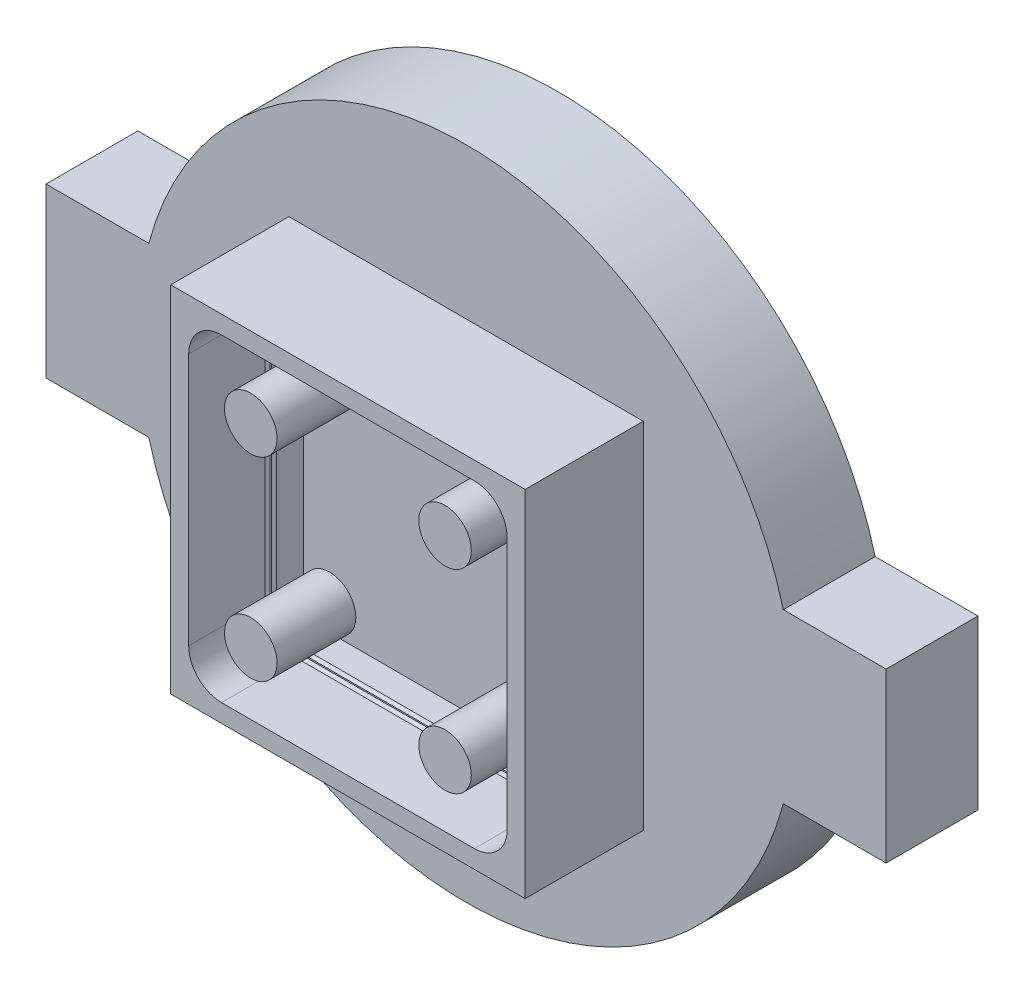
SolidWorks part; units mm, degrees
material "PLA"
ref_plane "Front Plane" through (0, 0, 0) normal (0, 0, 1) x (1, 0, 0)
ref_plane "Top Plane" through (0, 0, 0) normal (0, 1, 0) x (1, 0, 0)
ref_plane "Right Plane" through (0, 0, 0) normal (1, 0, 0) x (0, 0, -1)
sketch "Sketch1" plane through (0, 0, 0) normal (0, 0, 1) x (1, 0, 0)
  line L0 (-9.9216, -1.25) -> (-14.0216, -1.25) construction
  line L1 (14.0216, -1.25) -> (9.9216, -1.25) construction
  line L2 (14.0216, 1.25) -> (14.0216, -1.25) construction
  line L3 (-14.0216, -1.25) -> (-14.0216, 1.25) construction
  line L4 (-14.0216, 1.25) -> (-9.9216, 1.25) construction
  line L5 (9.9216, 1.25) -> (14.0216, 1.25) construction
  line L6 (-9.9216, -1.25) -> (-14.0216, -1.25)
  line L7 (14.0216, -1.25) -> (9.9216, -1.25)
  line L8 (14.0216, 1.25) -> (14.0216, -1.25)
  line L9 (-14.0216, -1.25) -> (-14.0216, 1.25)
  line L10 (-14.0216, 1.25) -> (-9.9216, 1.25)
  line L11 (9.9216, 1.25) -> (14.0216, 1.25)
  arc A0 (-9.9216, -1.25) -> (9.9216, -1.25) centre (0, 0) ccw construction
  arc A1 (9.9216, 1.25) -> (-9.9216, 1.25) centre (0, 0) ccw construction
  arc A2 (-9.9216, -1.25) -> (9.9216, -1.25) centre (0, 0) ccw
  arc A3 (9.9216, 1.25) -> (-9.9216, 1.25) centre (0, 0) ccw
  circle A4 centre (0, 0) radius 17.5
  dimension "D1" = 35
extrude "Boss-Extrude1" add sketch "Sketch1" along normal blind 3 contours A4
sketch "Sketch2" plane through (0, 0, 3) normal (0, 0, 1) x (1, 0, 0)
  circle A0 centre (0, 0) radius 17.5
extrude "Boss-Extrude2" add sketch "Sketch2" along normal blind 0.5
sketch "Sketch3" plane through (0, 0, 3.5) normal (0, 0, 1) x (1, 0, 0)
  line L1 (4.7, 4.7) -> (-4.7, 4.7)
  line L2 (4.7, 4.7) -> (4.7, -4.7)
  line L3 (4.7, -4.7) -> (-4.7, -4.7)
  line L4 (-4.7, 4.7) -> (-4.7, -4.7)
  line L5 (4.7, 4.7) -> (-4.7, -4.7) construction
  line L6 (4.7, -4.7) -> (-4.7, 4.7) construction
  line L7 (5.815, -5.815) -> (-5.815, -5.815)
  line L8 (5.815, -5.815) -> (5.815, 5.815)
  line L9 (5.815, 5.815) -> (-5.815, 5.815)
  line L10 (-5.815, -5.815) -> (-5.815, 5.815)
  line L11 (5.815, -5.815) -> (-5.815, 5.815) construction
  line L12 (5.815, 5.815) -> (-5.815, -5.815) construction
  line L13 (-6.75, -6.75) -> (6.75, -6.75)
  line L14 (-6.75, -6.75) -> (-6.75, 6.75)
  line L15 (-6.75, 6.75) -> (6.75, 6.75)
  line L16 (6.75, -6.75) -> (6.75, 6.75)
  line L17 (-6.75, -6.75) -> (6.75, 6.75) construction
  line L18 (-6.75, 6.75) -> (6.75, -6.75) construction
  circle A1 centre (0, 0) radius 17.5
  circle A2 centre (0, 0) radius 17.5 construction
  dimension "D2" = 9.4
  dimension "D3" = 11.63
  dimension "D4" = 13.5
  dimension "D1" = 0
extrude "Boss-Extrude3" add sketch "Sketch3" along normal blind 1.5 contours L1 L4 L3 L2 | L13 L16 L15 L14 L7 L10 L9 L8
fillet "Fillet1" radius 1 8 edges at (-5.815, -5.815, 4.25) (5.815, 5.815, 4.25) (-5.815, 5.815, 4.25) (4.7, -4.7, 4.25) (5.815, -5.815, 4.25) (-4.7, -4.7, 4.25) (-4.7, 4.7, 4.25) (4.7, 4.7, 4.25)
sketch "Sketch4" plane through (0, 0, 0) normal (0, 0, -1) x (-1, 0, 0)
  line L0 (0, -3.2) -> (0, -13.6813) construction
  line L1 (0, 0) -> (-15.8073, 0) construction
  line L2 (-16, 3.2) -> (-16, -3.2)
  line L3 (16, 3.2) -> (12.0835, 3.2)
  line L4 (16, 3.2) -> (16, -3.2)
  line L5 (16, -3.2) -> (12.0835, -3.2)
  line L7 (-12.0835, -3.2) -> (-16, -3.2)
  line L8 (-12.0835, 3.2) -> (-16, 3.2)
  arc A0 (12.0835, -3.2) -> (-12.0835, -3.2) centre (0, 0) cw
  arc A1 (12.0835, 3.2) -> (-12.0835, 3.2) centre (0, 0) ccw
  circle A2 centre (0, 0) radius 17.5
  circle A3 centre (0, 0) radius 17.5 construction
  dimension "D3" = 12.5
  dimension "D1" = 6.4
  dimension "D2" = 16
extrude "Cut-Extrude1" cut sketch "Sketch4" against normal blind 32.5
sketch "Sketch5" plane through (0, 0, 5) normal (0, 0, 1) x (1, 0, 0)
  circle A3 centre (0, 0) radius 3.94 construction
  circle A4 centre (-3.7, 3.7) radius 1
  circle A5 centre (3.7, 3.7) radius 1
  circle A6 centre (3.7, -3.7) radius 1
  circle A7 centre (-3.7, -3.7) radius 1
  arc A8 (-4.7, -3.7) -> (-3.7, -4.7) centre (-3.7, -3.7) ccw construction
  arc A9 (-3.7, 4.7) -> (-4.7, 3.7) centre (-3.7, 3.7) ccw construction
  dimension "D2" = 7.88
extrude "Boss-Extrude4" add sketch "Sketch5" along normal blind 3
sketch "Sketch6" plane through (0, 0, 8) normal (0, 0, 1) x (1, 0, 0)
  line L0 (0, 0) -> (0, -3.7) construction
  line L3 (0, 0) -> (3.3794, 0) construction
  line L14 (-6.065, 4.815) -> (-6.065, -4.815)
  line L15 (-4.815, -6.065) -> (4.815, -6.065)
  line L16 (6.065, -4.815) -> (6.065, 4.815)
  line L17 (4.815, 6.065) -> (-4.815, 6.065)
  line L18 (-6.065, 4.815) -> (-6.065, -4.815)
  line L19 (-4.815, -6.065) -> (4.815, -6.065)
  line L20 (6.065, -4.815) -> (6.065, 4.815)
  line L21 (4.815, 6.065) -> (-4.815, 6.065)
  line L38 (-6.75, -6.75) -> (6.75, -6.75)
  line L39 (6.75, -6.75) -> (6.75, 6.75)
  line L40 (6.75, 6.75) -> (-6.75, 6.75)
  line L41 (-6.75, 6.75) -> (-6.75, -6.75)
  line L46 (-6.75, -6.75) -> (6.75, -6.75)
  line L47 (6.75, -6.75) -> (6.75, 6.75)
  line L48 (6.75, 6.75) -> (-6.75, 6.75)
  line L49 (-6.75, 6.75) -> (-6.75, -6.75)
  arc A12 (-6.065, -4.815) -> (-4.815, -6.065) centre (-4.815, -4.815) ccw
  arc A13 (4.815, -6.065) -> (6.065, -4.815) centre (4.815, -4.815) ccw
  arc A14 (6.065, 4.815) -> (4.815, 6.065) centre (4.815, 4.815) ccw
  arc A15 (-4.815, 6.065) -> (-6.065, 4.815) centre (-4.815, 4.815) ccw
  arc A16 (-6.065, -4.815) -> (-4.815, -6.065) centre (-4.815, -4.815) ccw
  arc A17 (4.815, -6.065) -> (6.065, -4.815) centre (4.815, -4.815) ccw
  arc A18 (6.065, 4.815) -> (4.815, 6.065) centre (4.815, 4.815) ccw
  arc A19 (-4.815, 6.065) -> (-6.065, 4.815) centre (-4.815, 4.815) ccw
  dimension "D1" = 0.25
  dimension "D2" = 0
extrude "Boss-Extrude6" add sketch "Sketch6" against normal up to surface (3 mm away) up to face at (0, 0, 5)
chamfer "Chamfer1" distance 0.1 angle 45 16 edges at (-5.6989, 5.6989, 5) (0, 6.065, 5) (5.6989, 5.6989, 5) (6.065, 0, 5) (5.6989, -5.6989, 5) (0, -6.065, 5) (-5.6989, -5.6989, 5) (-6.065, 0, 5) (5.5221, 5.5221, 5) (0, 5.815, 5) (-5.5221, 5.5221, 5) (-5.815, 0, 5) (-5.5221, -5.5221, 5) (0, -5.815, 5) (5.5221, -5.5221, 5) (5.815, 0, 5)
